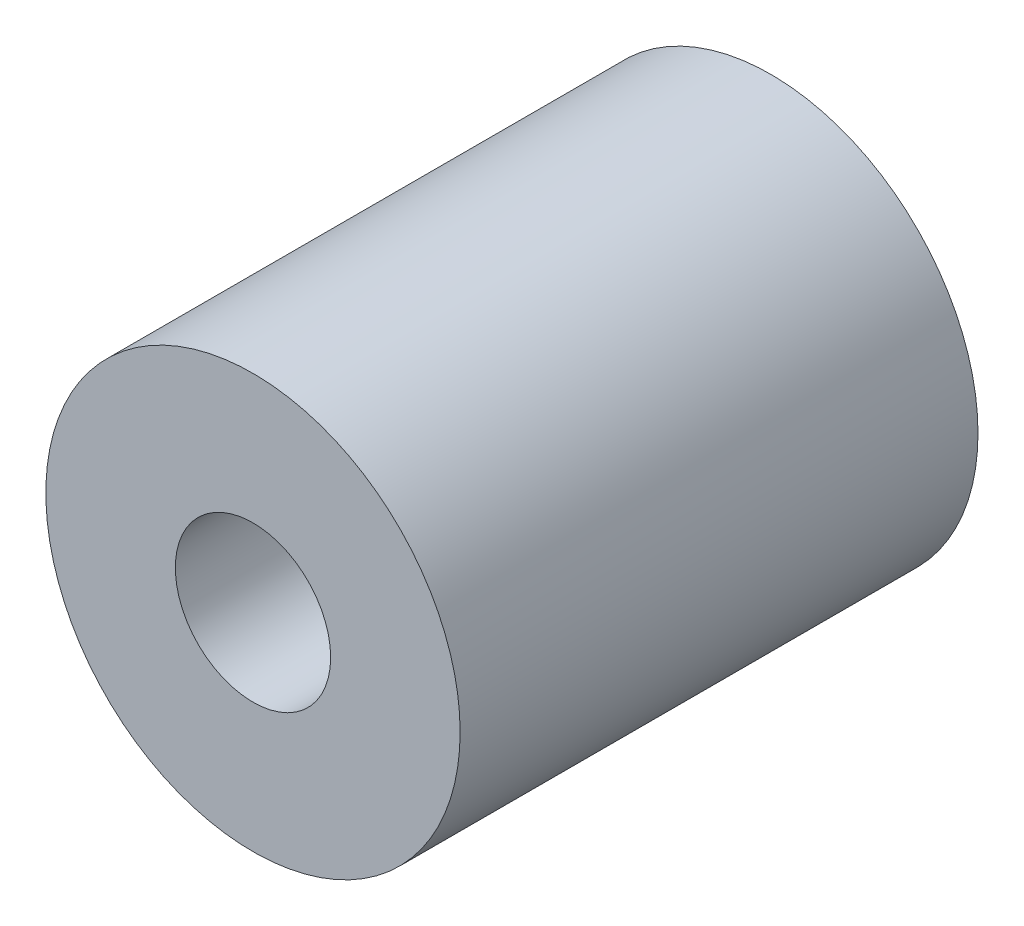
SolidWorks part; units mm, degrees
ref_plane "Front" through (0, 0, 0) normal (0, 0, 1) x (1, 0, 0)
ref_plane "Top" through (0, 0, 0) normal (0, 1, 0) x (1, 0, 0)
ref_plane "Right" through (0, 0, 0) normal (1, 0, 0) x (0, 0, -1)
sketch "草图1" plane through (0, 0, 0) normal (0, 0, 1) x (1, 0, 0)
  circle A0 centre (0, 0) radius 4
  circle A1 centre (0, 0) radius 1.5
extrude "凸台-拉伸1" add sketch "草图1" along normal blind 10
